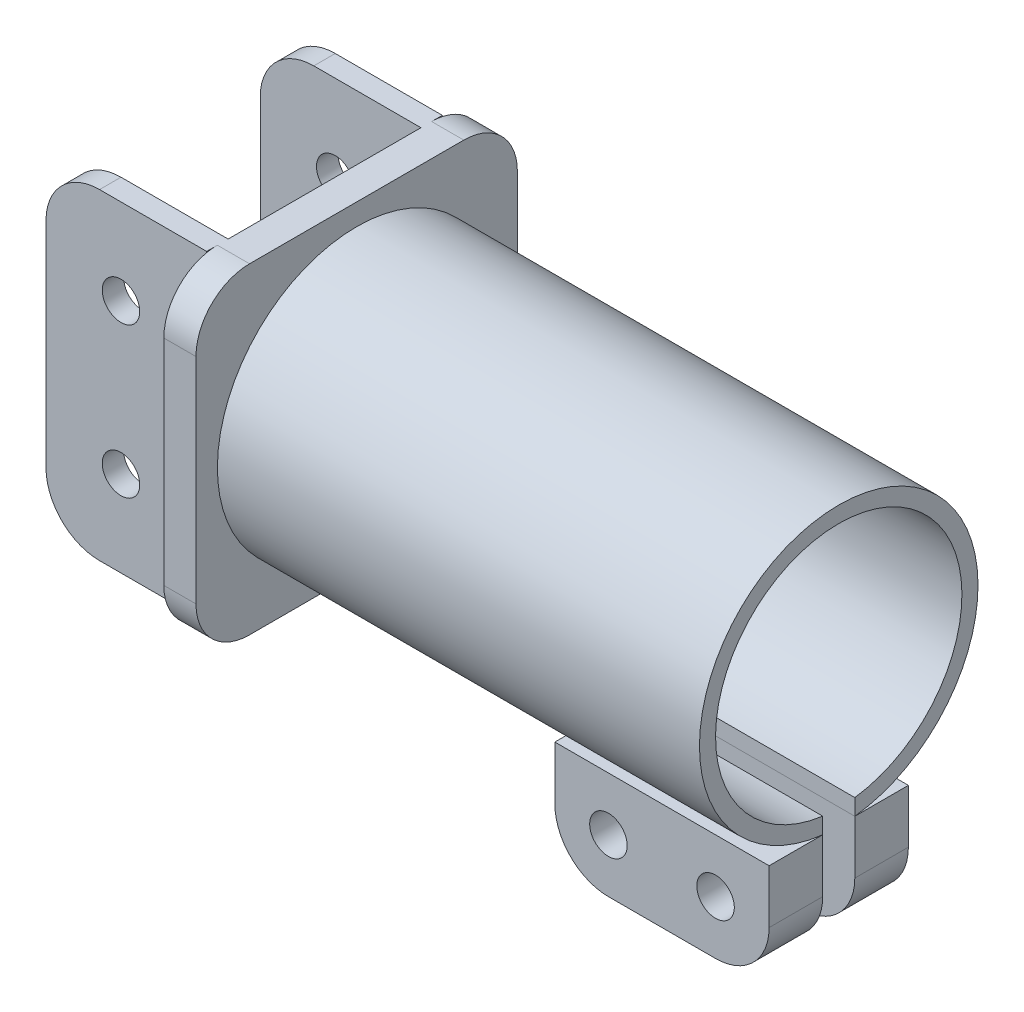
SolidWorks part; units mm, degrees
ref_plane "Front Plane" through (0, 0, 0) normal (0, 0, 1) x (1, 0, 0)
ref_plane "Top Plane" through (0, 0, 0) normal (0, 1, 0) x (1, 0, 0)
ref_plane "Right Plane" through (0, 0, 0) normal (1, 0, 0) x (0, 0, -1)
sketch "Sketch1" plane through (0, 0, 0) normal (1, 0, 0) x (0, 0, -1)
  circle A0 centre (0, 0) radius 13
  point P2 (0, 0)
  dimension "D1" = 26
extrude "Extrude-Thin1" add sketch "Sketch1" along normal blind 45 thin thin type one direction reverse wall 1.5
sketch "Sketch2" plane through (0, 0, 0) normal (-1, 0, 0) x (0, 0, 1)
  line L1 (-10, 15) -> (10, 15)
  line L2 (-15, 10) -> (-15, -10)
  line L3 (-10, -15) -> (10, -15)
  line L4 (15, 10) -> (15, -10)
  line L5 (-15, 15) -> (15, -15) construction
  line L6 (-15, -15) -> (15, 15) construction
  arc A0 (-15, -10) -> (-10, -15) centre (-10, -10) ccw
  arc A1 (10, -15) -> (15, -10) centre (10, -10) ccw
  arc A2 (10, 15) -> (15, 10) centre (10, 10) cw
  arc A3 (-10, 15) -> (-15, 10) centre (-10, 10) ccw
  point P0 (1.8765, -1.7942)
  dimension "D3" = 5
  dimension "D1" = 30
  dimension "D2" = 30
extrude "Boss-Extrude1" add sketch "Sketch2" along normal blind 3
sketch "Sketch3" plane through (-3, 0, 0) normal (-1, 0, 0) x (0, 0, 1)
  line L0 (10, 15) -> (-10, 15) construction
  line L1 (-11, 15) -> (-9, 15)
  line L2 (-11, 15) -> (-11, -15)
  line L3 (-11, -15) -> (-9, -15)
  line L4 (-9, 15) -> (-9, -15)
  line L5 (11, 15) -> (9, 15)
  line L6 (11, 15) -> (11, -15)
  line L7 (11, -15) -> (9, -15)
  line L8 (9, 15) -> (9, -15)
  line L9 (-10, -15) -> (10, -15) construction
  line L10 (0, -16.5) -> (0, 16.5) construction
  dimension "D1" = 9
  dimension "D2" = 9
  dimension "D3" = 2
  dimension "D4" = 2
extrude "Boss-Extrude2" add sketch "Sketch3" along normal blind 15
sketch "Sketch4" plane through (0, 0, 0) normal (0, 0, 1) x (1, 0, 0)
  line L0 (45, -13) -> (45, 13) construction
  line L1 (5, -7.3163) -> (45, -7.3163)
  line L2 (5, -7.3163) -> (5, -19.6344)
  line L3 (5, -19.6344) -> (45, -19.6344)
  line L4 (45, -7.3163) -> (45, -19.6344)
  dimension "D1" = 40
extrude "Cut-Extrude1" cut sketch "Sketch4" against normal mid plane 3
fillet "Fillet1" radius 5 4 edges at (-18, -15, -10) (-18, -15, 10) (-18, 15, -10) (-18, 15, 10)
sketch "Sketch5" plane through (0, 0, 11) normal (0, 0, 1) x (1, 0, 0)
  line L0 (16.5, 0) -> (-16.5, 0) construction
  circle A0 centre (-11, 7) radius 1.75
  circle A1 centre (-11, -7) radius 1.75
  point P4 (0, 0)
  point P5 (0, 0)
  point P6 (0, 0)
  point P11 (-11.6963, 8.884)
  dimension "D1" = 3.5
  dimension "D2" = 7
  dimension "D3" = 7
  dimension "D4" = 7
extrude "Cut-Extrude2" cut sketch "Sketch5" against normal through all
sketch "Sketch6" plane through (0, 0, -1.5) normal (0, 0, 1) x (1, 0, 0)
  line L0 (5, -12.9132) -> (45, -12.9132) construction
  line L1 (25, -12.9132) -> (45, -12.9132)
  line L2 (25, -12.9132) -> (25, -17.9132)
  line L3 (30, -22.9132) -> (40, -22.9132)
  line L4 (45, -12.9132) -> (45, -17.9132)
  line L5 (45, -12.9132) -> (45, 13) construction
  arc A0 (40, -22.9132) -> (45, -17.9132) centre (40, -17.9132) ccw
  arc A1 (25, -17.9132) -> (30, -22.9132) centre (30, -17.9132) ccw
  circle A2 centre (30, -17.9132) radius 1.75
  circle A3 centre (40, -17.9132) radius 1.75
  point P10 (45, -22.9132)
  point P13 (25, -22.9132)
  dimension "D3" = 5
  dimension "D4" = 3.5
  dimension "D1" = 20
  dimension "D2" = 10
extrude "Boss-Extrude3" add sketch "Sketch6" against normal blind 5 separate body
sketch "Sketch7" plane through (0, 0, 1.5) normal (0, 0, -1) x (-1, 0, 0)
  line L0 (-25, -12.9132) -> (-25, -17.9132) construction
  line L1 (-30, -22.9132) -> (-40, -22.9132) construction
  line L2 (-45, -17.9132) -> (-45, -12.9132) construction
  line L3 (-45, -12.9132) -> (-25, -12.9132) construction
  line L4 (-25, -12.9132) -> (-25, -17.9132)
  line L5 (-30, -22.9132) -> (-40, -22.9132)
  line L6 (-45, -17.9132) -> (-45, -12.9132)
  line L7 (-45, -12.9132) -> (-25, -12.9132)
  arc A0 (-45, -17.9132) -> (-40, -22.9132) centre (-40, -17.9132) ccw construction
  arc A1 (-45, -17.9132) -> (-40, -22.9132) centre (-40, -17.9132) ccw
  arc A2 (-30, -22.9132) -> (-25, -17.9132) centre (-30, -17.9132) ccw construction
  arc A3 (-30, -22.9132) -> (-25, -17.9132) centre (-30, -17.9132) ccw
  circle A4 centre (-30, -17.9132) radius 1.75 construction
  circle A5 centre (-40, -17.9132) radius 1.75 construction
  circle A6 centre (-30, -17.9132) radius 1.75
  circle A7 centre (-40, -17.9132) radius 1.75
extrude "Boss-Extrude4" add sketch "Sketch7" against normal blind 5 separate body
